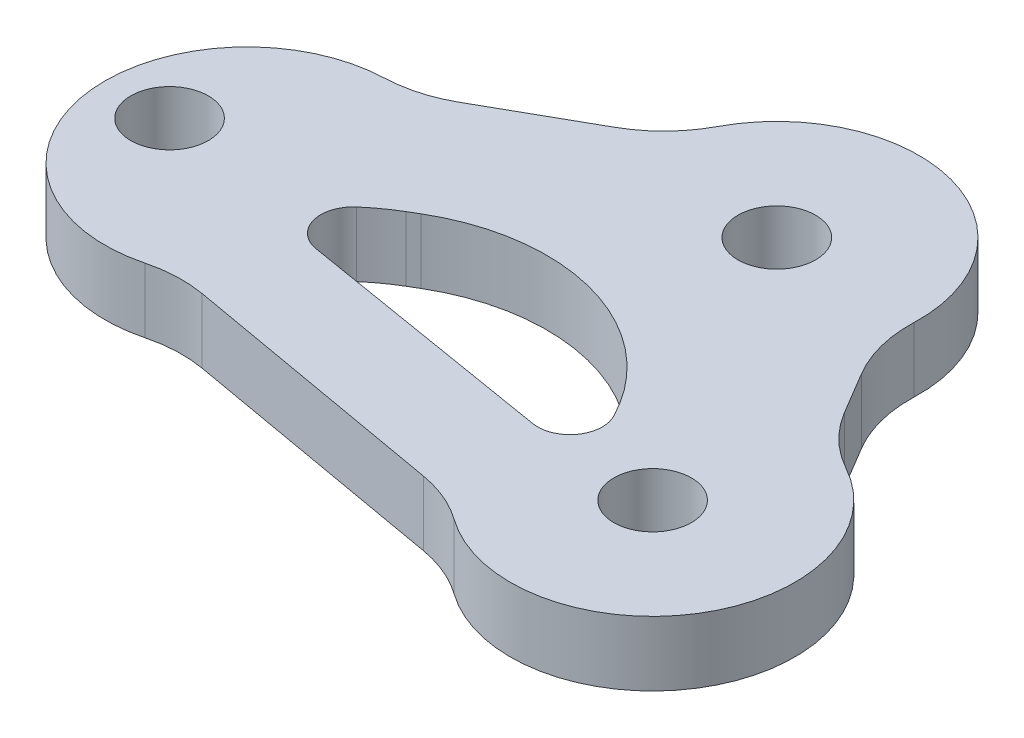
SolidWorks part; units mm, degrees
ref_plane "Front Plane" through (0, 0, 0) normal (0, 0, 1) x (1, 0, 0)
ref_plane "Top Plane" through (0, 0, 0) normal (0, 1, 0) x (1, 0, 0)
ref_plane "Right Plane" through (0, 0, 0) normal (1, 0, 0) x (0, 0, -1)
sketch "Sketch1" plane through (0, 0, 0) normal (0, 1, 0) x (1, 0, 0)
  line L0 (20.3127, -22.2126) -> (-19.8914, -15.5481)
  line L1 (34.3609, -1.8002) -> (30.4555, 4.7534) construction
  line L2 (-8.1351, 15.0915) -> (-23.4897, 6.4363) construction
  line L3 (-20.937, -20.5159) -> (20.6324, -27.8457) construction
  line L4 (-16.4342, -2.7606) -> (-17.9104, -3.6332)
  line L5 (18.6773, -32.078) -> (-21.5268, -25.4135) construction
  line L6 (-21.5232, 5.8477) -> (-22.9994, 4.975) construction
  line L7 (42.9512, 3.3189) -> (39.0459, 9.8725)
  line L8 (-13.0456, 23.8028) -> (-28.4002, 15.1476)
  line L9 (-22.6735, -30.364) -> (18.8959, -37.6938)
  arc A0 (25.5899, -15.0188) -> (-16.4342, -2.7606) centre (-1.1673, -28.5854) ccw
  circle A1 centre (-48.6756, -9.4013) radius 6
  arc A2 (32.8589, -32.9771) -> (20.6324, -27.8457) centre (15.423, -57.3899) ccw construction
  arc A3 (32.8589, -32.9771) -> (45.6329, -12.7065) centre (39.8333, -23.2119) ccw construction
  arc A4 (34.3609, -1.8002) -> (45.6329, -12.7065) centre (60.132, 13.5571) ccw construction
  arc A5 (26.2448, 21.1555) -> (30.4555, 4.7534) centre (56.2266, 20.1107) ccw construction
  arc A6 (26.2448, 21.1555) -> (3.6468, 27.1883) centre (14.2521, 21.5734) ccw construction
  arc A7 (-8.1351, 15.0915) -> (3.6468, 27.1883) centre (-22.8666, 41.2255) ccw construction
  arc A8 (-37.1172, 2.5905) -> (-23.4897, 6.4363) centre (-38.2212, 32.5702) ccw construction
  arc A9 (-37.1172, 2.5905) -> (-33.6673, -21.0181) centre (-36.6756, -9.4013) ccw construction
  arc A10 (-20.937, -20.5159) -> (-33.6673, -21.0181) centre (-26.1465, -50.0601) ccw construction
  circle A11 centre (14.2521, 21.5734) radius 6
  circle A12 centre (39.8333, -23.2119) radius 6
  arc A13 (20.3127, -22.2126) -> (25.5899, -15.0188) centre (21.1304, -17.2799) ccw
  arc A14 (-22.3598, -6.8469) -> (-19.8914, -15.5481) centre (-19.0737, -10.6154) ccw
  arc A15 (-17.9104, -3.6332) -> (-22.3598, -6.8469) centre (-2.6434, -29.458) ccw
  arc A16 (-28.9319, 0.6902) -> (-21.5268, -25.4135) centre (-19.0737, -10.6154) ccw construction
  arc A17 (-22.9994, 4.975) -> (-28.9319, 0.6902) centre (-2.6434, -29.458) ccw construction
  arc A18 (34.509, -10.4966) -> (-21.5232, 5.8477) centre (-1.1673, -28.5854) ccw construction
  arc A19 (18.6773, -32.078) -> (34.509, -10.4966) centre (21.1304, -17.2799) ccw construction
  arc A20 (36.2387, 20.8072) -> (39.0459, 9.8725) centre (56.2266, 20.1107) ccw
  arc A21 (36.2387, 20.8072) -> (-5.191, 31.8673) centre (14.2521, 21.5734) ccw
  arc A22 (-13.0456, 23.8028) -> (-5.191, 31.8673) centre (-22.8666, 41.2255) ccw
  arc A23 (-37.4852, 12.5838) -> (-28.4002, 15.1476) centre (-38.2212, 32.5702) ccw
  arc A24 (-37.4852, 12.5838) -> (-31.1603, -30.6988) centre (-36.6756, -9.4013) ccw
  arc A25 (-22.6735, -30.364) -> (-31.1603, -30.6988) centre (-26.1465, -50.0601) ccw
  arc A26 (27.0469, -41.1147) -> (18.8959, -37.6938) centre (15.423, -57.3899) ccw
  arc A27 (27.0469, -41.1147) -> (50.4659, -3.9519) centre (39.8333, -23.2119) ccw
  arc A28 (42.9512, 3.3189) -> (50.4659, -3.9519) centre (60.132, 13.5571) ccw
  circle A29 centre (-48.6756, -9.4013) radius 16 construction
  circle A30 centre (14.2521, 21.5734) radius 16 construction
  circle A31 centre (39.8333, -23.2119) radius 16 construction
  arc A32 (32.8589, -32.9771) -> (45.6329, -12.7065) centre (39.8333, -23.2119) ccw construction
  point P75 (-46.8041, -9.4013)
  point P76 (0, 0)
  point P77 (-48.6756, -9.4013)
  point P78 (0, 0)
  dimension "D1" = 12
  dimension "D2" = 12
  dimension "D3" = 30
  dimension "D4" = 12
  dimension "D5" = 12
  dimension "D6" = 5
  dimension "D7" = 3.6468
  dimension "D8" = 14.2521
  dimension "D9" = 15.423
  dimension "D10" = 20.3127
  dimension "D11" = 20.6324
  dimension "D12" = 21.1304
  dimension "D13" = 25.5899
  dimension "D14" = 26.2448
  dimension "D15" = 30.4555
  dimension "D16" = 32.8589
  dimension "D17" = 34.3609
  dimension "D18" = 2.6434
  dimension "D19" = 8.1351
  dimension "D20" = 16.4342
  dimension "D21" = 20.937
  dimension "D22" = 23.4897
  dimension "D23" = 2.5905
  dimension "D24" = 2.7606
  dimension "D25" = 10
extrude "Boss-Extrude1" add sketch "Sketch1" along normal blind 10
